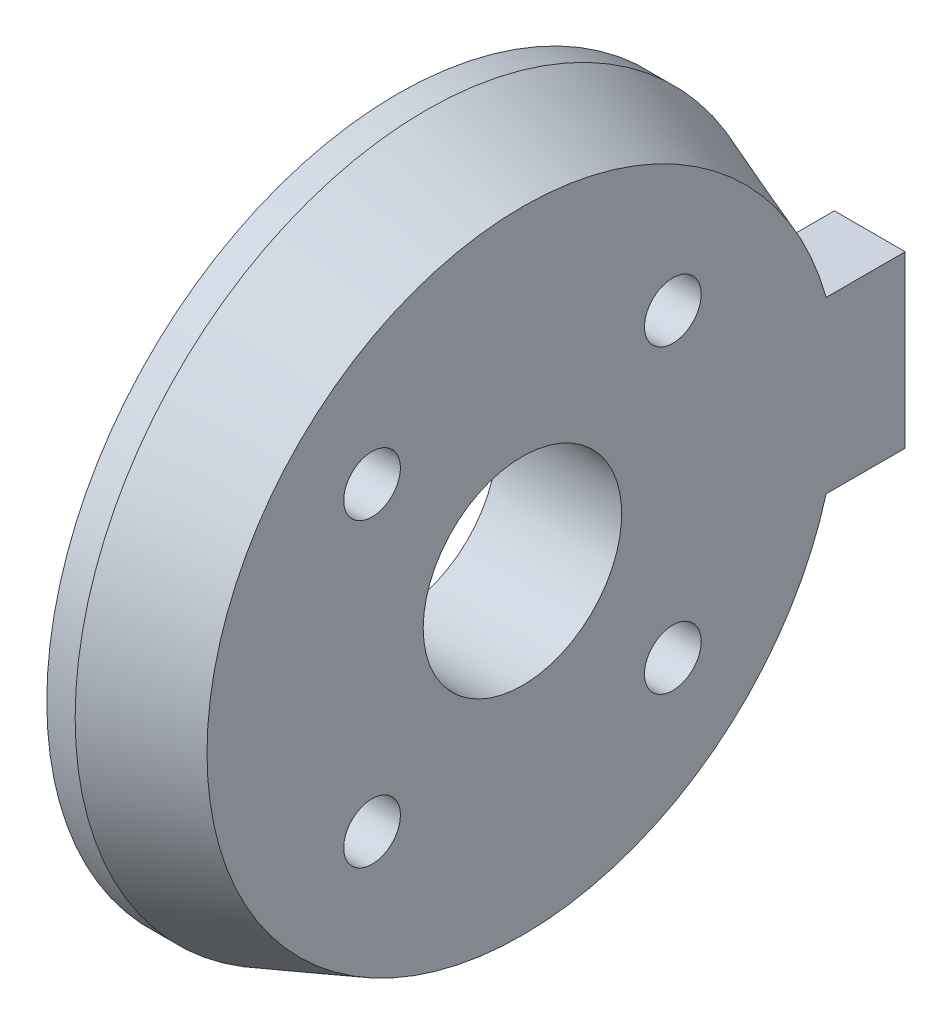
SolidWorks part; units mm, degrees
ref_plane "Front Plane" through (0, 0, 0) normal (0, 0, 1) x (1, 0, 0)
ref_plane "Top Plane" through (0, 0, 0) normal (0, 1, 0) x (1, 0, 0)
ref_plane "Right Plane" through (0, 0, 0) normal (1, 0, 0) x (0, 0, -1)
sketch "Sketch2" plane through (0, 0, 0) normal (0, 0, 1) x (1, 0, 0)
  line L0 (0, 0) -> (51.0154, 0) construction
  line L1 (0, 24.75) -> (2, 24.75)
  line L2 (2, 24.75) -> (8.8, 22.25)
  line L3 (8.8, 22.25) -> (8.8, 7)
  line L4 (8.8, 7) -> (0, 7)
  line L5 (0, 7) -> (0, 24.75)
  dimension "D1" = 8.8
  dimension "D2" = 2
  dimension "D3" = 2.5
  dimension "D4" = 14
  dimension "D5" = 49.5
revolve "Revolve1" add sketch "Sketch2" angle 360 about L0
sketch "Sketch3" plane through (8.8, 0, 0) normal (1, 0, 0) x (0, 0, -1)
  line L0 (0, 0) -> (10.6066, 10.6066) construction
  line L1 (0, 0) -> (5.0555, 0) construction
  circle A0 centre (10.6066, 10.6066) radius 2
  circle A1 centre (10.6066, -10.6066) radius 2
  circle A2 centre (-10.6066, -10.6066) radius 2
  circle A3 centre (-10.6066, 10.6066) radius 2
  point P14 (0, 0)
  dimension "D2" = 4
  dimension "D1" = 45
  dimension "D3" = 15
  dimension "D4" = 4
extrude "Cut-Extrude1" cut sketch "Sketch3" against normal blind 5
sketch "Sketch4" plane through (8.8, 0, 0) normal (1, 0, 0) x (0, 0, -1)
  line L0 (0, 0) -> (15, 0) construction
  line L1 (15, 6) -> (27, 6)
  line L2 (15, 6) -> (15, -6)
  line L3 (15, -6) -> (27, -6)
  line L4 (27, 6) -> (27, -6)
  dimension "D1" = 12
  dimension "D2" = 12
  dimension "D3" = 15
extrude "Boss-Extrude1" add sketch "Sketch4" against normal blind 5
